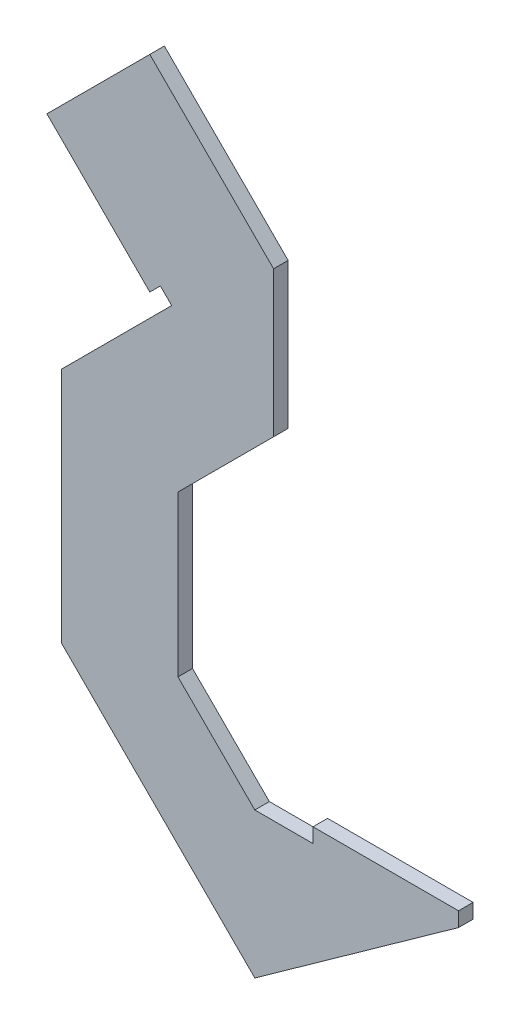
SolidWorks part; units mm, degrees
material "PBT General Purpose"
ref_plane "Front Plane" through (0, 0, 0) normal (0, 0, 1) x (1, 0, 0)
ref_plane "Top Plane" through (0, 0, 0) normal (0, 1, 0) x (1, 0, 0)
ref_plane "Right Plane" through (0, 0, 0) normal (1, 0, 0) x (0, 0, -1)
sketch "Sketch1" plane through (0, 0, 0) normal (0, 0, 1) x (1, 0, 0)
  line L0 (0, 0) -> (-1, 0)
  line L1 (-1, 0) -> (-1, -0.1)
  line L2 (-1, -0.1) -> (-1.4, -0.1)
  line L6 (-2.728, 0.228) -> (-1.4, -1.1)
  line L7 (-1.4, -1.1) -> (0, -0.1)
  line L8 (0, -0.1) -> (0, 0)
  line L10 (0, 0) -> (0.5, 0) construction
  line L11 (-3.4142, 3.9142) -> (0.5, 0) construction
  line L12 (-1.4, -0.1) -> (-1.928, 0.428)
  line L13 (-1.928, 0.428) -> (-1.928, 1.5282)
  line L14 (-1.928, 1.5282) -> (-1.271, 2.1852)
  line L15 (-1.271, 2.1852) -> (-1.271, 3.1852)
  line L16 (-1.271, 3.1852) -> (-2.1215, 4.0358)
  line L17 (-2.1215, 4.0358) -> (-2.8286, 3.3286)
  line L18 (-2.8286, 3.3286) -> (-2.1215, 2.6215)
  line L19 (-2.1215, 2.6215) -> (-2.049, 2.694)
  line L20 (-2.049, 2.694) -> (-1.9713, 2.6163)
  line L21 (-1.9713, 2.6163) -> (-2.728, 1.8596)
  line L22 (-2.728, 1.8596) -> (-2.728, 0.228)
  dimension "D1" = 1
  dimension "D2" = 0.1
  dimension "D3" = 0.4
  dimension "D4" = 0.5
  dimension "D5" = 45
  dimension "D6" = 0.1
  dimension "D7" = 0.8
  dimension "D8" = 0.8
  dimension "D9" = 1
  dimension "D10" = 1
  dimension "D11" = 1
  dimension "D12" = 135
  dimension "D13" = 1
extrude "Boss-Extrude1" add sketch "Sketch1" along normal mid plane 0.1 contours L6 L7 L8 L0 L1 L2 L12 L13 L14 L15 L16 L17 L18 L19 L20 L21 L22
